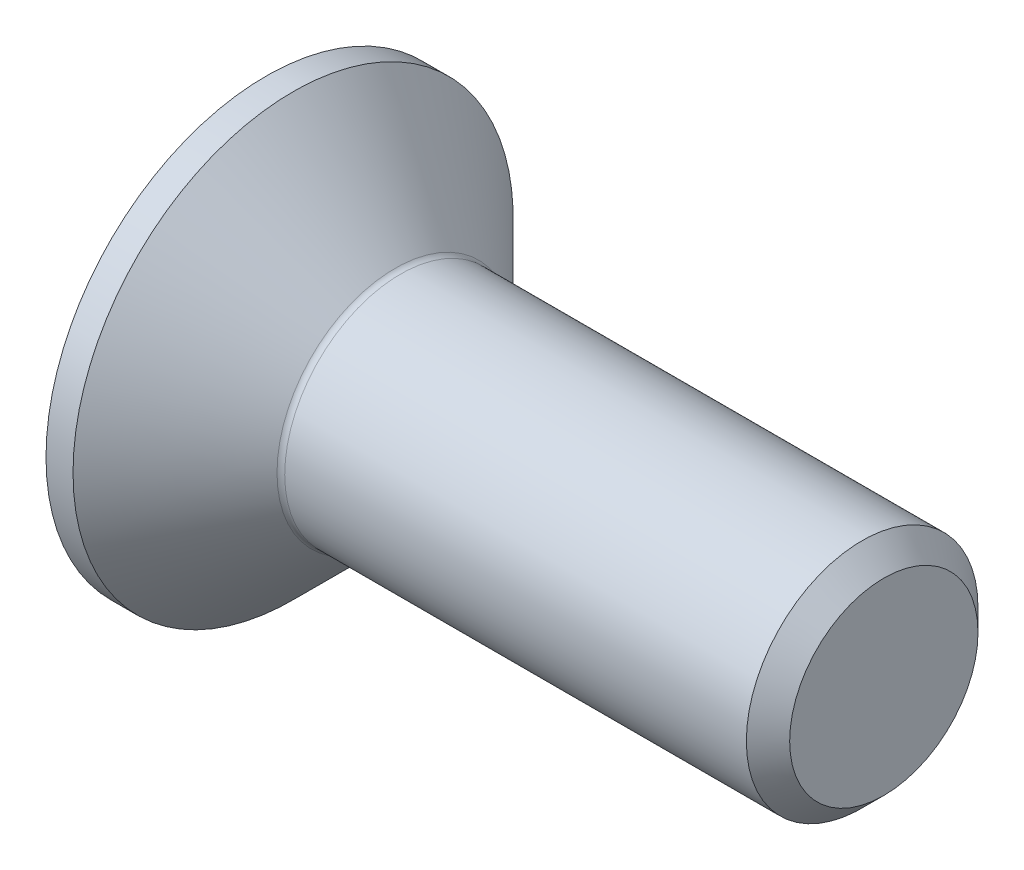
SolidWorks part; units mm, degrees
ref_plane "Plane1" through (0, 0, 0) normal (0, 0, 1) x (1, 0, 0)
ref_plane "Plane2" through (0, 0, 0) normal (0, 1, 0) x (1, 0, 0)
ref_plane "Plane3" through (0, 0, 0) normal (1, 0, 0) x (0, 0, -1)
sketch "BodySke" plane through (0, 0, 0) normal (0, 0, 1) x (1, 0, 0)
  line L0 (0, 0) -> (0, 2.85)
  line L1 (0.35, 2.85) -> (1.7, 1.5)
  line L2 (0, 2.85) -> (0.35, 2.85)
  line L3 (1.7, 1.5) -> (7.7195, 1.5)
  line L4 (8, 1.2195) -> (8, 0)
  line L5 (8, 0) -> (0, 0)
  line L6 (0, 0) -> (127, 0) construction
  line L7 (0.35, -2.85) -> (1.7, -1.5) construction
  line L8 (8, 1.2195) -> (7.7195, 1.5)
  line L9 (0, -2.85) -> (0.35, -2.85) construction
  line L10 (8, -1.2195) -> (7.7195, -1.5) construction
  line L11 (2.2, 7.85) -> (2.2, -14.375) construction
  line L12 (3.2, 16.35) -> (3.2, -5.875) construction
  dimension "Diameter" = 3
  dimension "Head_ht" = 1.7
  dimension "Length" = 8
  dimension "Body_ch_ang" = 45
  dimension "Head_dia" = 5.7
  dimension "Minor_dia" = 2.439
  dimension "Head_ang" = 90
  dimension "Advance" = 0.5
  dimension "Thread_nom" = 4.8
revolve "BaseBody" add sketch "BodySke" angle 360 about L6
cosmetic thread "ThreadCosmetic" [suppressed] parameters "Thread_length"=4.8, "Thread_minor"=2.439
fillet "Fillet1" radius 0.1 1 edges at (1.7, 0, 1.5)
sketch "Sketch2" plane through (0, 0, 0) normal (0, 0, 1) x (1, 0, 0)
  line L0 (0, 1.01) -> (1.2, 1.01)
  line L1 (1.2, 1.01) -> (1.7831, 0)
  line L2 (0, 0) -> (127, 0) construction
  line L3 (1.7831, 0) -> (0, 0)
  line L4 (0, 0) -> (0, 1.01)
  line L5 (0, -1.01) -> (1.2, -1.01) construction
  line L6 (0, 0) -> (47.625, 0) construction
  line L8 (0, 2.85) -> (0, -2.85) construction
  dimension "D2" = 60
  dimension "PreBroach_depth" = 1.2
  dimension "PreBroach_dia" = 2.02
revolve "PreBroach" cut sketch "Sketch2" angle 360 about L6
sketch "Sketch3" plane through (0, 0, 0) normal (-1, 0, 0) x (0, 0, 1)
  line L0 (-1.01, -0.5831) -> (-1.01, 0.5831)
  line L1 (-1.01, 0.5831) -> (0, 1.1662)
  line L2 (0, 1.1662) -> (1.01, 0.5831)
  line L3 (1.01, 0.5831) -> (1.01, -0.5831)
  line L4 (1.01, -0.5831) -> (0, -1.1662)
  line L5 (0, -1.1662) -> (-1.01, -0.5831)
  dimension "D1" = 1.01
  dimension "D2" = 1.01
  dimension "D3" = 2.02
  dimension "Hex_size" = 2.02
extrude "Hex" cut sketch "Sketch3" against normal blind 1.2
sketch "ThdSchSke" plane through (0, 0, 0) normal (0, 0, 1) x (1, 0, 0)
  line L0 (3.2, -1.2195) -> (3.0036, -1.5)
  line L1 (3.2, -1.2195) -> (3.3964, -1.5)
  line L2 (3.3964, -1.5) -> (3.3964, -1.875)
  line L3 (-3.175, 0) -> (5.1513, 0) construction
  line L4 (0, 2.85) -> (0, -2.85) construction
  line L5 (3.3964, -1.875) -> (3.0036, -1.875)
  line L6 (3.0036, -1.875) -> (3.0036, -1.5)
  dimension "Thread_minor" = 2.439
  dimension "Diameter" = 3
  dimension "Start" = 3.2
  dimension "SideAngle" = 55
  dimension "VeeAngle" = 70
  dimension "Overcut" = 3.75
revolve "ThreadSchematic" [suppressed] cut sketch "ThdSchSke" angle 360 about L3
pattern_linear "ThdSchPat" [suppressed]
equation "\"Thread_minor@ThreadCosmetic\"  =  \"Minor_dia@BodySke\""
equation "\"D1@Sketch3\" = \"Hex_size@Sketch3\" / 2"
equation "\"D2@Sketch3\" = \"D1@Sketch3\""
equation "\"D3@Sketch3\" = \"Hex_size@Sketch3\""
equation "\"Thread_length@ThreadCosmetic\" = ((sgn( (\"Length@BodySke\" - \"Advance@BodySke\" * 1.5 - \"Head_ht@BodySke\" ) - \"Thread_nom@BodySke\" )-1)*( (\"Length@BodySke\" - \"Advance@BodySke\" * 1.5 - \"Head_ht@BodySke\" ) - \"Thread_nom@BodySke\" ))/-2+ \"Thread_nom@BodySke\""
equation "\"Thread_minor@ThdSchSke\" = \"Minor_dia@BodySke\""
equation "\"Diameter@ThdSchSke\" = \"Diameter@BodySke\""
equation "\"Overcut@ThdSchSke\" = \"Diameter@BodySke\" * 1.25"
equation "\"Start@ThdSchSke\" = 0.000001 + \"Length@BodySke\" - \"Thread_length@ThreadCosmetic\"  '---Countersunk---"
equation "\"Num_threads@ThdSchPat\" = int( \"Thread_length@ThreadCosmetic\" / \"Advance@BodySke\" + 0.999 )  + 1"
equation "\"Advance@ThdSchPat\" = \"Thread_length@ThreadCosmetic\" /  (\"Num_threads@ThdSchPat\" - 1) 'relax it"
equation "\"Num_threads@ThdSchPat\" = \"Num_threads@ThdSchPat\" - sgn( \"Num_threads@ThdSchPat\" - 1) '---chamfered tips only---"
